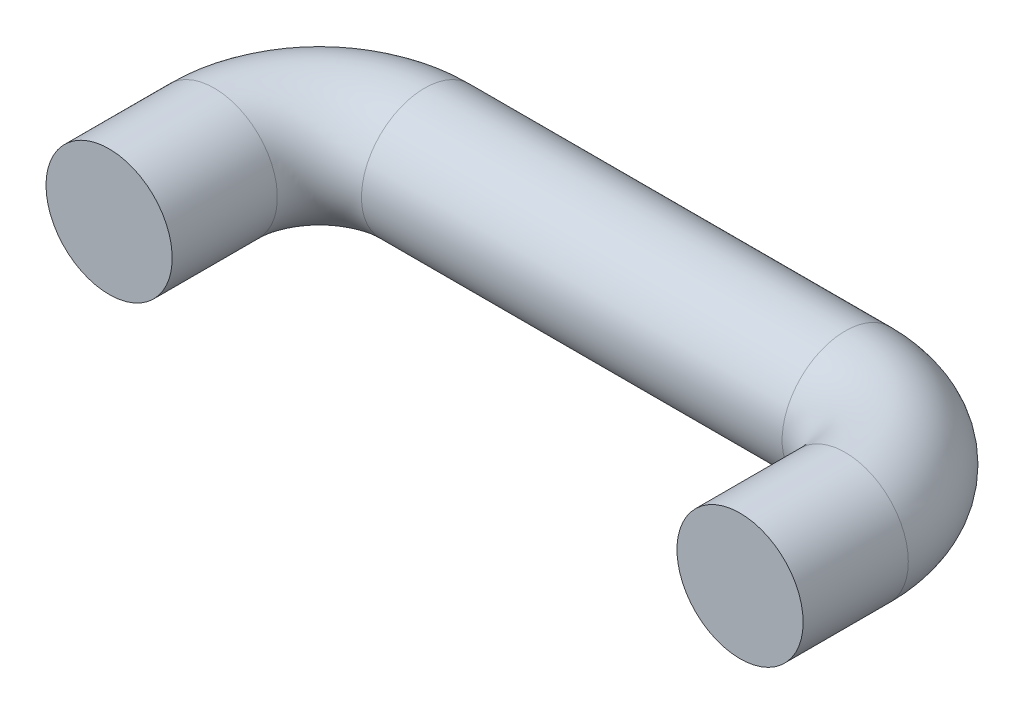
SolidWorks part; units mm, degrees
ref_plane "Płaszczyzna przednia" through (0, 0, 0) normal (0, 0, 1) x (1, 0, 0)
ref_plane "Płaszczyzna górna" through (0, 0, 0) normal (0, 1, 0) x (1, 0, 0)
ref_plane "Płaszczyzna prawa" through (0, 0, 0) normal (1, 0, 0) x (0, 0, -1)
sketch "Szkic1" plane through (0, 0, 0) normal (0, 1, 0) x (1, 0, 0)
  line L0 (0, 43.3664) -> (0, -25.2489) construction
  line L1 (45, 0) -> (-45, 0)
  line L2 (-45, -15) -> (-45, 15)
  line L3 (-55, 15) -> (-35, 15)
  line L4 (-30, 20) -> (-30, 25)
  line L5 (-60, 20) -> (-60, 25)
  line L6 (-60, -20) -> (-60, -25)
  line L7 (-30, -20) -> (-30, -25)
  line L8 (-55, -15) -> (-35, -15)
  line L9 (55, -15) -> (35, -15)
  line L10 (30, -20) -> (30, -25)
  line L11 (60, -20) -> (60, -25)
  line L12 (60, 20) -> (60, 25)
  line L13 (30, 20) -> (30, 25)
  line L14 (55, 15) -> (35, 15)
  line L15 (45, -15) -> (45, 15)
  arc A0 (60, 20) -> (55, 15) centre (55, 20) cw
  arc A1 (35, 15) -> (30, 20) centre (35, 20) cw
  arc A2 (60, -20) -> (55, -15) centre (55, -20) ccw
  arc A3 (35, -15) -> (30, -20) centre (35, -20) ccw
  arc A4 (-30, 20) -> (-35, 15) centre (-35, 20) cw
  arc A5 (-55, 15) -> (-60, 20) centre (-55, 20) cw
  arc A6 (-35, -15) -> (-30, -20) centre (-35, -20) cw
  arc A7 (-55, -15) -> (-60, -20) centre (-55, -20) ccw
  point P26 (0, 0)
  point P28 (60, 15)
  point P31 (30, 15)
  point P34 (60, -15)
  point P37 (30, -15)
  point P40 (-30, 15)
  point P43 (-60, 15)
  point P46 (-30, -15)
  point P49 (-60, -15)
  dimension "D1" = 5
ref_plane "Płaszczyzna1" through (-60, 0, 25) normal (0, 0, -1) x (-1, 0, 0)
sketch "Szkic2" plane through (-60, 0, 25) normal (0, 0, -1) x (-1, 0, 0)
  circle A0 centre (0, 0) radius 3
sweep "Wyciągnięcie po ścieżce1" add profiles "Szkic2" path "Szkic1"
